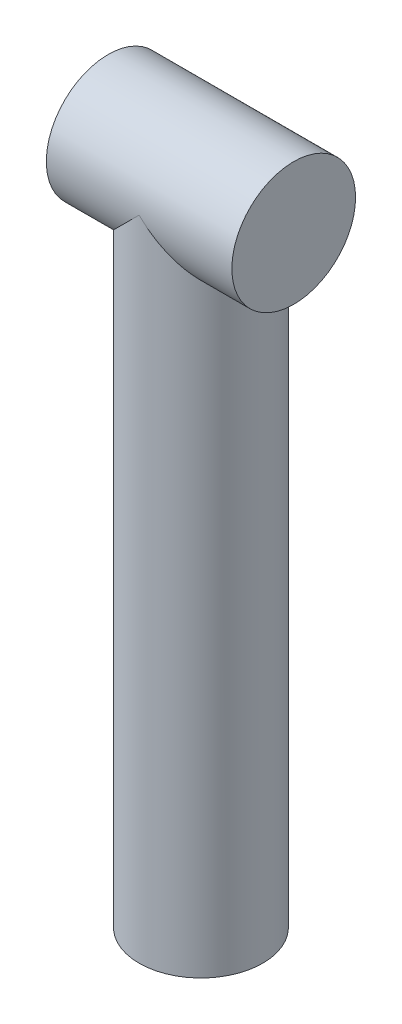
SolidWorks part; units mm, degrees
ref_plane "前视基准面" through (0, 0, 0) normal (0, 0, 1) x (1, 0, 0)
ref_plane "上视基准面" through (0, 0, 0) normal (0, 1, 0) x (1, 0, 0)
ref_plane "右视基准面" through (0, 0, 0) normal (1, 0, 0) x (0, 0, -1)
sketch "草图1" plane through (0, 0, 0) normal (0, 1, 0) x (1, 0, 0)
  circle A0 centre (0, 0) radius 20
  dimension "D1" = 40
extrude "凸台-拉伸1" add sketch "草图1" along normal blind 209.5
sketch "草图2" plane through (0, 0, 0) normal (1, 0, 0) x (0, 0, -1)
  line L0 (20, 209.5) -> (-20, 209.5) construction
  line L1 (20, 0) -> (20, 209.5) construction
  circle A0 centre (0, 209.5) radius 20
extrude "凸台-拉伸2" add sketch "草图2" along normal mid plane 60
